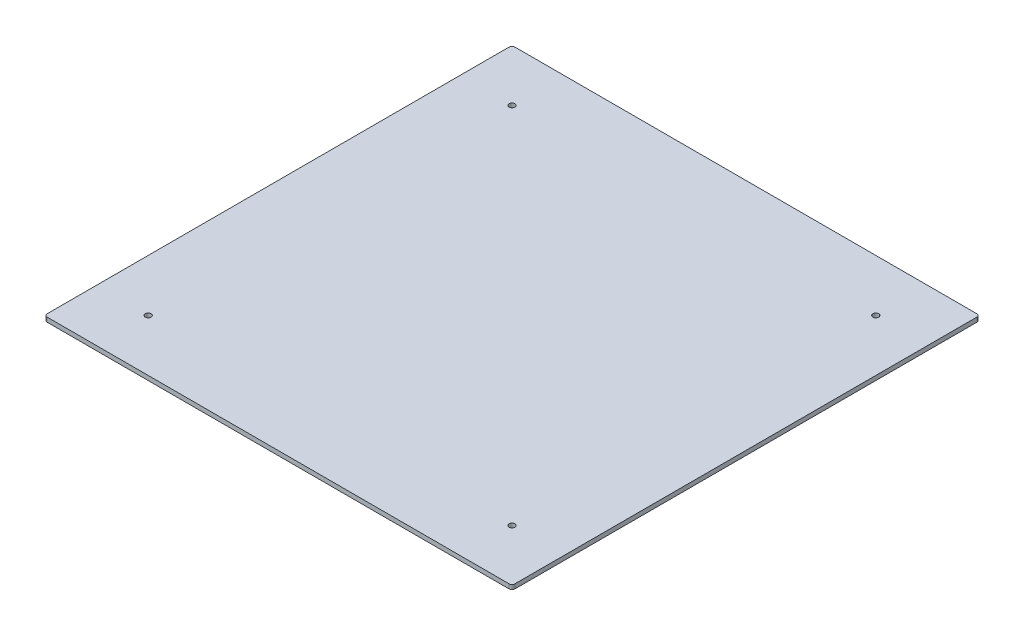
SolidWorks part; units mm, degrees
ref_plane "Front Plane" through (0, 0, 0) normal (0, 0, 1) x (1, 0, 0)
ref_plane "Top Plane" through (0, 0, 0) normal (0, 1, 0) x (1, 0, 0)
ref_plane "Right Plane" through (0, 0, 0) normal (1, 0, 0) x (0, 0, -1)
sketch "Sketch1" plane through (0, 0, 0) normal (0, 1, 0) x (1, 0, 0)
  line L1 (157.5, -157.5) -> (-157.5, -157.5)
  line L2 (157.5, -157.5) -> (157.5, 157.5)
  line L3 (157.5, 157.5) -> (-157.5, 157.5)
  line L4 (-157.5, -157.5) -> (-157.5, 157.5)
  line L5 (157.5, -157.5) -> (-157.5, 157.5) construction
  line L6 (157.5, 157.5) -> (-157.5, -157.5) construction
  point P0 (0, 0)
  dimension "D1" = 315
  dimension "D2" = 315
extrude "Boss-Extrude1" add sketch "Sketch1" along normal blind 3
sketch "Sketch3" plane through (0, 3, 0) normal (0, 1, 0) x (1, 0, 0)
  line L0 (157.5, 157.5) -> (-157.5, 157.5) construction
  line L1 (-122.5, -122.5) -> (122.5, -122.5) construction
  line L2 (-122.5, -122.5) -> (-122.5, 122.5) construction
  line L3 (-122.5, 122.5) -> (122.5, 122.5) construction
  line L4 (122.5, -122.5) -> (122.5, 122.5) construction
  line L5 (-122.5, -122.5) -> (122.5, 122.5) construction
  line L6 (-122.5, 122.5) -> (122.5, -122.5) construction
  line L7 (157.5, -157.5) -> (157.5, 157.5) construction
  circle A0 centre (-122.5, 122.5) radius 2
  circle A1 centre (122.5, 122.5) radius 2
  circle A2 centre (122.5, -122.5) radius 2
  circle A3 centre (-122.5, -122.5) radius 2
  point P0 (0, 0)
  dimension "D3" = 4
  dimension "D1" = 35
  dimension "D2" = 35
extrude "Cut-Extrude1" cut sketch "Sketch3" against normal blind 10
fillet "Fillet1" radius 2 4 edges at (-157.5, 1.5, -157.5) (157.5, 1.5, -157.5) (157.5, 1.5, 157.5) (-157.5, 1.5, 157.5)
sketch "Sketch2" plane through (0, 0, 0) normal (0, 1, 0) x (1, 0, 0)
  line L0 (0, -212.9179) -> (0, 212.9179) construction
  line L1 (-223.4465, 0) -> (223.4465, 0) construction
  point P4 (0, 0)
  point P8 (0, 0)
